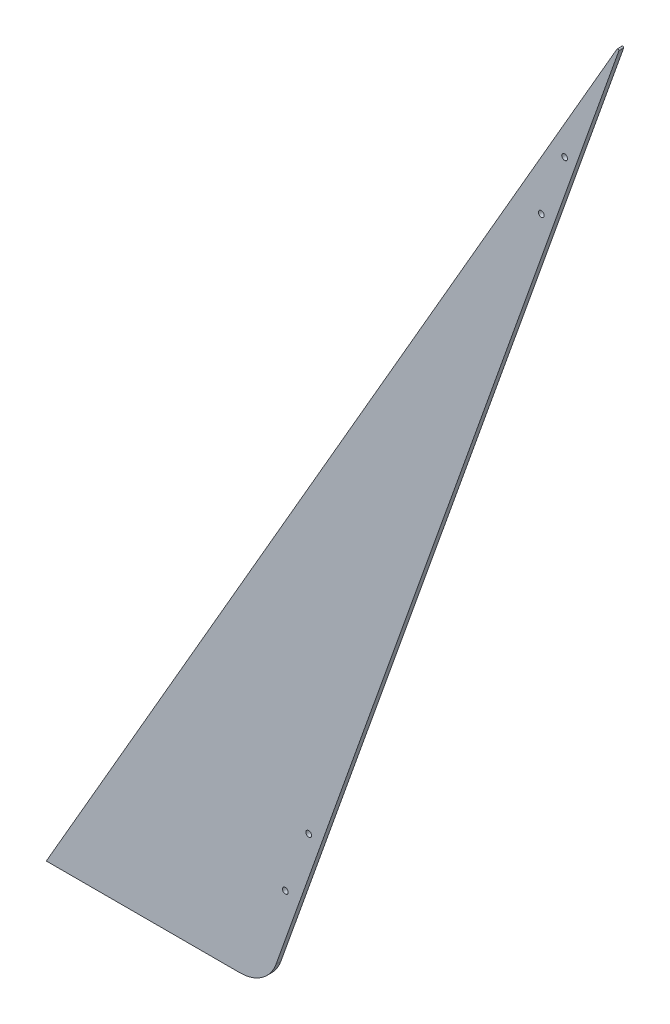
SolidWorks part; units mm, degrees
material "Acrylic (Medium-high impact)"
ref_plane "Front Plane" through (0, 0, 0) normal (0, 0, 1) x (1, 0, 0)
ref_plane "Top Plane" through (0, 0, 0) normal (0, 1, 0) x (1, 0, 0)
ref_plane "Right Plane" through (0, 0, 0) normal (1, 0, 0) x (0, 0, -1)
sketch "Sketch1" plane through (0, 0, 0) normal (0, 0, 1) x (1, 0, 0)
  line L0 (0, 0) -> (230, 0)
  line L1 (230, 0) -> (600.4443, 1040)
  line L2 (600.4443, 1040) -> (0, 0)
  point P9 (-651.2838, 485.8996)
  point P10 (-1043.8487, 602.6663)
  dimension "D1" = 1040
  dimension "D2" = 230
  dimension "D3" = 60
extrude "Boss-Extrude1" add sketch "Sketch1" along normal blind 5
fillet "Fillet1" radius 40 1 edges at (230, 0, 2.5)
fillet "Fillet2" radius 1 1 edges at (600.4443, 1040, 2.5)
sketch "Sketch2" plane through (0, 0, 5) normal (0, 0, 1) x (1, 0, 0)
  circle A0 centre (249.1477, 97.7586) radius 3
  circle A1 centre (273.4945, 161.2505) radius 3
  circle A2 centre (515.8855, 842.0449) radius 3
  circle A3 centre (540.2323, 905.5369) radius 3
  point P8 (0, 0)
  dimension "D1" = 6
extrude "Cut-Extrude1" cut sketch "Sketch2" against normal through all
